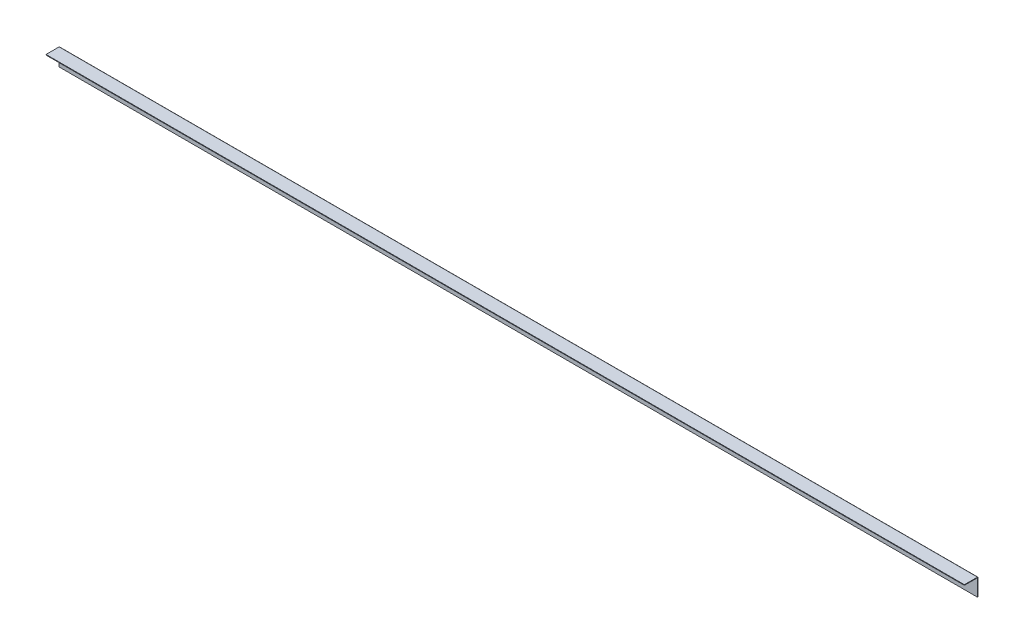
SolidWorks part; units mm, degrees
ref_plane "Front Plane" through (0, 0, 0) normal (0, 0, 1) x (1, 0, 0)
ref_plane "Top Plane" through (0, 0, 0) normal (0, 1, 0) x (1, 0, 0)
ref_plane "Right Plane" through (0, 0, 0) normal (1, 0, 0) x (0, 0, -1)
sketch "Sketch1" plane through (0, 0, 0) normal (1, 0, 0) x (0, 0, -1)
  line L0 (0, 0) -> (73, 0)
  line L1 (73, 0) -> (73, -93)
  line L2 (0, -3) -> (70, -3)
  line L3 (70, -3) -> (70, -93)
  line L4 (0, 0) -> (0, -3)
  line L5 (70, -93) -> (73, -93)
  dimension "D1" = 73
  dimension "D2" = 93
  dimension "D3" = 3
extrude "Boss-Extrude1" add sketch "Sketch1" along normal blind 4922
fillet "Fillet1" radius 3 2 edges at (2461, 0, -73) (2461, -3, -70)
equation "\"unequal_angleBar_Side_RT_3mm_length\"= 2922"
equation "\"D1@Boss-Extrude1\"= \"boxLength\" - 90 - 90 + 2"
equation "\"CarBeamWidth\"=700.0"
equation "\"WheelWidth\"=650.0"
equation "\"Wheel_FrontBoxDistance\"=1390.0"
equation "\"boxLength\"=5100.0"
equation "\"boxWidth\"=1930.0"
equation "\"MetalSheet_3mm_length\"=5030.0"
equation "\"MetalSheet_3mm_width\"=1923.0"
equation "\"MetalSheet_3mm_FloorCut_L_length\"=1764.0"
equation "\"MetalSheet_3mm_FloorCut_L_disdance\"=1665.0"
equation "\"MetalSheet_3mm_FloorCut_R_length\"=1764.0"
equation "\"MetalSheet_3mm_FloorCut_R_disdance\"=1665.0"
equation "\"indoorHeight\"=1940.0"
equation "\"indoorHeight_para\"=25.0"
equation "\"rearLightHeight_para\"=265.0"
equation "\"doorColumnBar_A_FR_3mm_length_Cut\"=2310.0"
equation "\"A\"=0.0"
equation "\"haveDoor_R\"=1"
equation "\"side_door_bottom_R_3mm_length\"=1934.0"
equation "\"side_door_bottom_R_3mm_toFrontDistance\"=1583.0"
equation "\"1Bar_Side_RF_3mm_length\"=1493.0"
equation "\"1Bar_Side_RB_3mm_length\"=1493.0"
equation "\"DoorSeparator_RF_3mm_withHinge_toFrontDistance\"=1673.0"
equation "\"DoorSeparator_RF_3mm_withHinge_exist\"=1"
equation "\"DoorSeparator_RB_3mm_withHinge_toFrontDistance\"=3427.0"
equation "\"DoorSeparator_RB_3mm_withHinge_exist\"=1"
equation "\"Door_R1_L_open_Single_toFrontDistance\"=2547.5"
equation "\"Door_R1_L_open_Single_exist\"=1"
equation "\"door_base_long7_R1_L_open_Single_height\"=1890.0"
equation "\"door_base_short7_R1_L_open_Single_height\"=1890.0"
equation "\"door_base_short7_R1_L_open_Single_width\"=864"
equation "\"Door_R1_R_open_Single_toFrontDistance\"=3422.0"
equation "\"Door_R1_R_open_Single_exist\"=1"
equation "\"door_base_long7_R1_R_open_Single_height\"=1890.0"
equation "\"door_base_short7_R1_R_open_Single_height\"=1890.0"
equation "\"door_base_short7_R1_R_open_Single_width\"=864"
equation "\"x\"=66.0"
equation "\"door_base_double_BL_height\"=1890.0"
equation "\"door_base_short7_BL_Single_height\"=1890.0"
equation "\"door_base_short7_BL_Single_width\"=864"
equation "\"door_base_long7_BR_Single_height\"=1890.0"
equation "\"door_base_short7_BR_Single_height\"=1890.0"
equation "\"door_base_short7_BR_Single_width\"=864"
equation "\"da\"=62.0"
equation "\"SquareTube_length\"=1923.0"
equation "\"channelSteel_length\"=5030.0"
equation "\"SquareTube_inFront_AvgDistance\"=285.0"
equation "\"SquareTube_inFront_TotalCount\"=5"
equation "\"SquareTube_inFront1_cutDepth50_R\"=0.5"
equation "\"SquareTube_inFront1_cutDepth50_L\"=0.5"
equation "\"SquareTube_inFront2_cutDepth50_R\"=0.5"
equation "\"SquareTube_inFront2_cutDepth50_L\"=0.5"
equation "\"SquareTube_inFront3_cutDepth50_R\"=0.5"
equation "\"SquareTube_inFront3_cutDepth50_L\"=0.5"
equation "\"SquareTube_inFront4_cutDepth50_R\"=0.5"
equation "\"SquareTube_inFront4_cutDepth50_L\"=0.5"
equation "\"SquareTube_inFront5_cutDepth50_R\"=50"
equation "\"SquareTube_inFront5_cutDepth50_L\"=50"
equation "\"SquareTube_inFront6_cutDepth50_R\"=50"
equation "\"SquareTube_inFront6_cutDepth50_L\"=50"
equation "\"SquareTube_inFront7_cutDepth50_R\"=50"
equation "\"SquareTube_inFront7_cutDepth50_L\"=50"
equation "\"SquareTube_inFront8_cutDepth50_R\"=50"
equation "\"SquareTube_inFront8_cutDepth50_L\"=50"
equation "\"SquareTube_inFront9_cutDepth50_R\"=50"
equation "\"SquareTube_inFront9_cutDepth50_L\"=50"
equation "\"SquareTube_inFront10_cutDepth50_R\"=50"
equation "\"SquareTube_inFront10_cutDepth50_L\"=50"
equation "\"SquareTube_inFront11_cutDepth50_R\"=50"
equation "\"SquareTube_inFront11_cutDepth50_L\"=50"
equation "\"SquareTube_inFront12_cutDepth50_R\"=50"
equation "\"SquareTube_inFront12_cutDepth50_L\"=50"
equation "\"SquareTube_inFront13_cutDepth50_R\"=50"
equation "\"SquareTube_inFront13_cutDepth50_L\"=50"
equation "\"SquareTube_inFront14_cutDepth50_R\"=50"
equation "\"SquareTube_inFront14_cutDepth50_L\"=50"
equation "\"SquareTube_inBack_AvgDistance\"=333.125"
equation "\"SquareTube_inBack_TotalCount\"=9"
equation "\"SquareTube_inBack1_cutDepth50_R\"=50"
equation "\"SquareTube_inBack1_cutDepth50_L\"=50"
equation "\"SquareTube_inBack2_cutDepth50_R\"=50"
equation "\"SquareTube_inBack2_cutDepth50_L\"=50"
equation "\"SquareTube_inBack3_cutDepth50_R\"=50"
equation "\"SquareTube_inBack3_cutDepth50_L\"=50"
equation "\"SquareTube_inBack4_cutDepth50_R\"=50"
equation "\"SquareTube_inBack4_cutDepth50_L\"=50"
equation "\"SquareTube_inBack5_cutDepth50_R\"=50"
equation "\"SquareTube_inBack5_cutDepth50_L\"=50"
equation "\"SquareTube_inBack6_cutDepth50_R\"=0.5"
equation "\"SquareTube_inBack6_cutDepth50_L\"=0.5"
equation "\"SquareTube_inBack7_cutDepth50_R\"=0.5"
equation "\"SquareTube_inBack7_cutDepth50_L\"=0.5"
equation "\"SquareTube_inBack8_cutDepth50_R\"=0.5"
equation "\"SquareTube_inBack8_cutDepth50_L\"=0.5"
